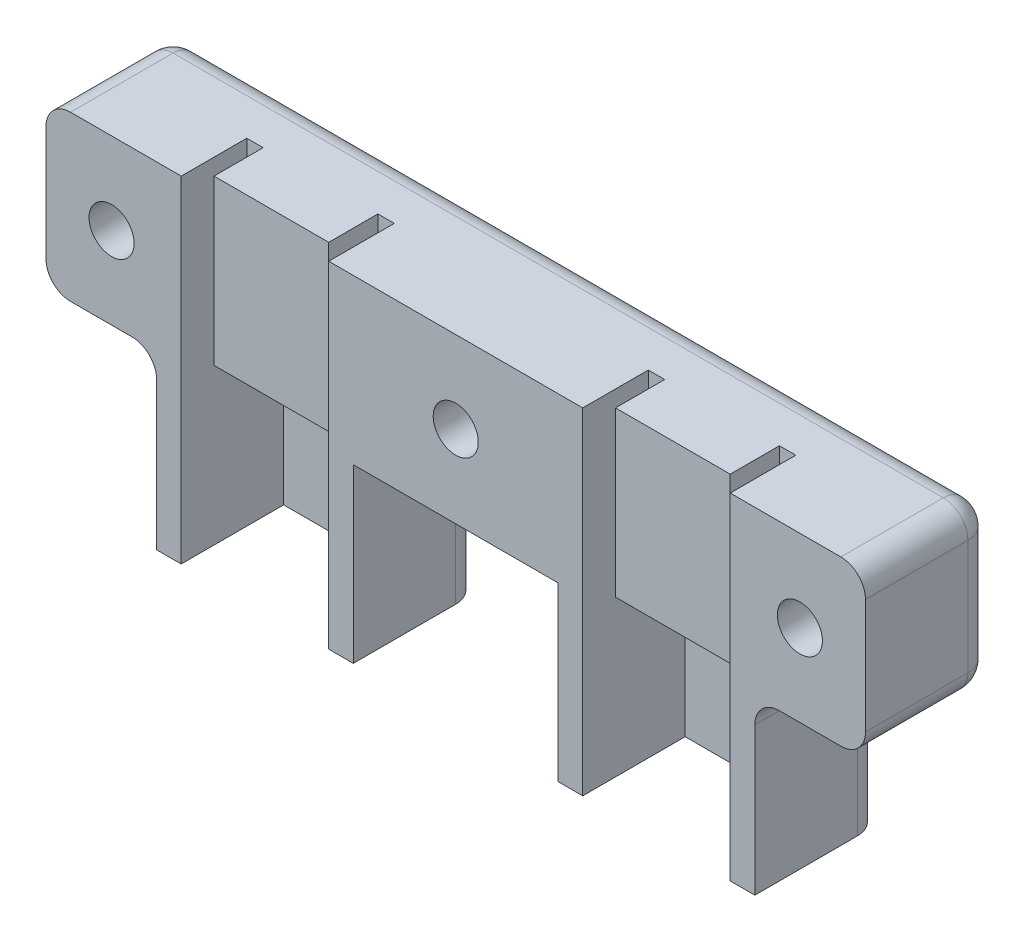
SolidWorks part; units mm, degrees
ref_plane "Front Plane" through (0, 0, 0) normal (0, 0, 1) x (1, 0, 0)
ref_plane "Top Plane" through (0, 0, 0) normal (0, 1, 0) x (1, 0, 0)
ref_plane "Right Plane" through (0, 0, 0) normal (1, 0, 0) x (0, 0, -1)
sketch "Sketch1" plane through (0, 0, 0) normal (0, 1, 0) x (1, 0, 0)
  line L0 (-32.5165, -1.8398) -> (-32.5165, 13.6602)
  line L1 (-32.5165, 13.6602) -> (67.4835, 13.6602)
  line L2 (17.4835, 19.0774) -> (17.4835, -21.7565) construction
  line L3 (-0.0165, 0.1602) -> (-14.0165, 0.1602)
  line L4 (-14.0165, 0.1602) -> (-14.0165, 6.1602)
  line L5 (-14.0165, 6.1602) -> (-16.0165, 6.1602)
  line L6 (-16.0165, 6.1602) -> (-16.0165, 1.6364)
  line L7 (-32.5165, -1.8398) -> (-16.0165, -1.8398)
  line L8 (-16.0165, -1.8398) -> (-16.0165, 1.6364)
  line L9 (-7.0165, 12.4346) -> (-7.0165, -12.2705) construction
  line L10 (1.9835, -1.8398) -> (1.9835, 1.6364)
  line L11 (1.9835, 6.1602) -> (1.9835, 1.6364)
  line L12 (-0.0165, 6.1602) -> (1.9835, 6.1602)
  line L13 (-0.0165, 0.1602) -> (-0.0165, 6.1602)
  line L15 (34.9835, 0.1602) -> (34.9835, 6.1602)
  line L16 (34.9835, 6.1602) -> (32.9835, 6.1602)
  line L17 (32.9835, 6.1602) -> (32.9835, 1.6364)
  line L18 (32.9835, -1.8398) -> (32.9835, 1.6364)
  line L19 (50.9835, -1.8398) -> (50.9835, 1.6364)
  line L20 (67.4835, -1.8398) -> (50.9835, -1.8398)
  line L21 (50.9835, 6.1602) -> (50.9835, 1.6364)
  line L22 (48.9835, 6.1602) -> (50.9835, 6.1602)
  line L23 (48.9835, 0.1602) -> (48.9835, 6.1602)
  line L24 (34.9835, 0.1602) -> (48.9835, 0.1602)
  line L25 (67.4835, -1.8398) -> (67.4835, 13.6602)
  line L26 (1.9835, -1.8398) -> (32.9835, -1.8398)
  point P15 (41.9835, 0.1602)
  point P18 (-7.0165, 0.1602)
  point P32 (17.4835, 13.6602)
  dimension "D1" = 7
  dimension "D2" = 8
  dimension "D3" = 2
  dimension "D4" = 6
  dimension "D5" = 15.5
  dimension "D6" = 16.5
extrude "Boss-Extrude1" add sketch "Sketch1" along normal blind 20
sketch "Sketch2" plane through (0, 0, 0) normal (0, -1, 0) x (1, 0, 0)
  line L0 (-17.5165, 1.8398) -> (-17.5165, -12.1602)
  line L1 (-32.5165, 1.8398) -> (-16.0165, 1.8398) construction
  line L2 (-17.5165, -12.1602) -> (3.4835, -12.1602)
  line L3 (3.4835, -12.1602) -> (3.4835, 1.8398)
  line L4 (-16.0165, 1.8398) -> (-16.0165, -6.1602) construction
  line L5 (1.9835, -6.1602) -> (1.9835, 1.8398) construction
  line L6 (17.4835, 8.9785) -> (17.4835, -37.4649) construction
  line L7 (-32.5165, -13.6602) -> (-32.5165, 1.8398) construction
  line L8 (52.4835, 1.8398) -> (52.4835, -12.1602)
  line L9 (52.4835, -12.1602) -> (31.4835, -12.1602)
  line L10 (31.4835, -12.1602) -> (31.4835, 1.8398)
  dimension "D1" = 1.5
  dimension "D2" = 1.5
  dimension "D3" = 14
  dimension "D4" = 50
extrude "Extrude-Thin3" add sketch "Sketch2" along normal blind 21 thin thin type mid plane wall 3
sketch "Sketch3" plane through (0, 0, -13.6602) normal (0, 0, -1) x (-1, 0, 0)
  line L3 (-17.4835, 44.3817) -> (-17.4835, -29.4557) construction
  circle A0 centre (24.5165, 10) radius 2.75
  circle A1 centre (-59.4835, 10) radius 2.75
  circle A2 centre (-17.4835, 10) radius 2.75
  dimension "D1" = 5.5
extrude "Cut-Extrude1" cut sketch "Sketch3" against normal through all
fillet "Fillet2" radius 3 16 edges at (29.9835, -10.5, -13.6602) (53.9835, -10.5, -13.6602) (67.4835, 0, -5.9102) (67.4835, 10, -13.6602) (67.4835, 20, -5.9102) (17.4835, 20, -13.6602) (-32.5165, 20, -5.9102) (-32.5165, 0, -5.9102) (-32.5165, 10, -13.6602) (53.9835, 0, -5.9102)
sketch "Sketch4" plane through (0, 0, -13.6602) normal (0, 0, -1) x (-1, 0, 0)
  line L0 (16.0165, -21) -> (-1.9835, -21) construction
  line L1 (-4.9835, -21) -> (-4.9835, 0) construction
  circle A0 centre (2.5165, -9) radius 1.25
  circle A1 centre (11.5165, -9) radius 1.25
  dimension "D1" = 12
  dimension "D2" = 2.5
  dimension "D4" = 7.5
  dimension "D3" = 9
extrude "Cut-Extrude2" cut sketch "Sketch4" against normal blind 10
